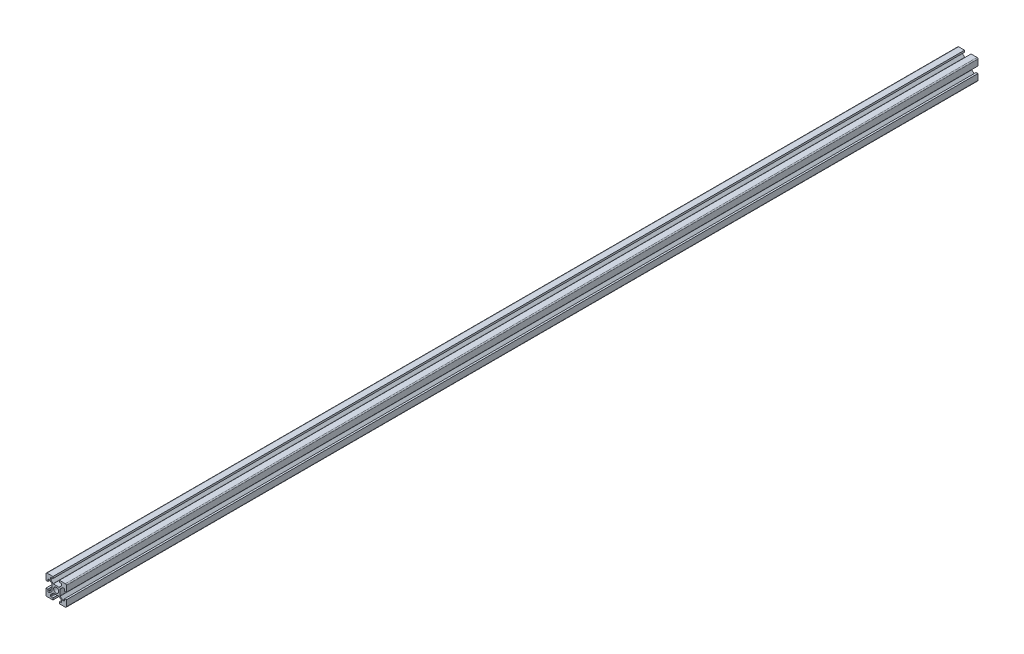
SolidWorks part; units mm, degrees
material "1060 Alloy"
ref_plane "Front Plane" through (0, 0, 0) normal (0, 0, 1) x (1, 0, 0)
ref_plane "Top Plane" through (0, 0, 0) normal (0, 1, 0) x (1, 0, 0)
ref_plane "Right Plane" through (0, 0, 0) normal (1, 0, 0) x (0, 0, -1)
sketch "Sketch1" plane through (0, 0, 0) normal (0, 0, 1) x (1, 0, 0)
  line L0 (20, 0) -> (-8.059, 28.059) construction
  line L1 (0, 0) -> (6.8, 0)
  line L2 (0, 0) -> (0, 6.8)
  line L3 (0, 20) -> (6.8, 20)
  line L4 (20, 0) -> (20, 6.8)
  line L5 (6.8, 20) -> (6.8, 18.2)
  line L6 (20, 20) -> (8.2322, 8.2322) construction
  line L7 (12.95, 6.1) -> (7.05, 6.1)
  line L8 (13.9, 7.05) -> (13.9, 12.95)
  line L9 (12.95, 13.9) -> (7.05, 13.9)
  line L10 (6.1, 7.05) -> (6.1, 12.95)
  line L11 (13.9, 6.1) -> (6.1, 13.9) construction
  line L12 (13.9, 13.9) -> (6.1, 6.1) construction
  line L13 (4.55, 16.4) -> (7.05, 13.9)
  line L14 (13.2, 18.2) -> (13.2, 20)
  line L15 (1.8, 6.8) -> (0, 6.8)
  line L16 (0, 13.2) -> (0, 20)
  line L17 (0, 13.2) -> (1.8, 13.2)
  line L18 (10, 10) -> (10, 13.9) construction
  line L19 (16.4, 4.55) -> (13.9, 7.05)
  line L20 (4.55, 16.4) -> (4.55, 18.2)
  line L21 (4.55, 18.2) -> (6.8, 18.2)
  line L22 (13.2, 18.2) -> (15.45, 18.2)
  line L23 (15.45, 18.2) -> (15.45, 16.4)
  line L24 (15.45, 16.4) -> (12.95, 13.9)
  line L25 (16.4, 4.55) -> (18.2, 4.55)
  line L26 (18.2, 4.55) -> (18.2, 6.8)
  line L27 (20, 6.8) -> (18.2, 6.8)
  line L28 (18.2, 13.2) -> (20, 13.2)
  line L29 (18.2, 13.2) -> (18.2, 15.45)
  line L30 (18.2, 15.45) -> (16.4, 15.45)
  line L31 (16.4, 15.45) -> (13.9, 12.95)
  line L32 (1.8, 4.55) -> (3.6, 4.55)
  line L33 (3.6, 15.45) -> (6.1, 12.95)
  line L34 (3.6, 15.45) -> (1.8, 15.45)
  line L35 (1.8, 15.45) -> (1.8, 13.2)
  line L36 (0, 13.2) -> (1.8, 13.2)
  line L37 (1.8, 6.8) -> (0, 6.8)
  line L38 (3.6, 4.55) -> (6.1, 7.05)
  line L39 (1.8, 6.8) -> (1.8, 4.55)
  line L40 (15.45, 3.6) -> (12.95, 6.1)
  line L41 (4.55, 3.6) -> (7.05, 6.1)
  line L42 (4.55, 1.8) -> (4.55, 3.6)
  line L43 (6.8, 1.8) -> (4.55, 1.8)
  line L44 (6.8, 1.8) -> (6.8, 0)
  line L45 (15.45, 3.6) -> (15.45, 1.8)
  line L46 (15.45, 1.8) -> (13.2, 1.8)
  line L47 (13.2, 0) -> (13.2, 1.8)
  line L48 (13.2, 20) -> (20, 20)
  line L49 (20, 13.2) -> (20, 20)
  line L50 (13.2, 0) -> (20, 0)
  line L51 (6.1, 6.1) -> (-5.5045, -5.5045) construction
  circle A0 centre (10, 10) radius 2.5
  point P25 (10, 16.4)
  point P39 (13.2, 19.1)
  point P46 (0.9, 6.8)
  dimension "D3" = 5
  dimension "D2" = 20
  dimension "D4" = 7.8
  dimension "D5" = 7.8
  dimension "D6" = 6.8
  dimension "D7" = 6.8
  dimension "D8" = 1.8
  dimension "D9" = 10.9
  dimension "D10" = 1.8
  dimension "D11" = 10.9
  dimension "D12" = 20
extrude "Boss-Extrude1" add sketch "Sketch1" along normal blind 894.4 contours L47 L50 L4 L27 L26 L25 L19 L8 L31 L30 L29 L28 L49 L48 L14 L22 L23 L24 L9 L13 L20 L21 L5 L3 L16 L17 L35 L34 L33 L10 L38 L32 L39 L15 L2 L1 L44 L43 L42 L41 L7 L40 L45 L46 A0
fillet "Fillet1" radius 1 4 edges at (20, 20, 447.2) (20, 0, 447.2) (0, 0, 447.2) (0, 20, 447.2)
fillet "Fillet2" radius 0.5 6 edges at (4.55, 18.2, 447.2) (4.55, 16.4, 447.2) (7.05, 13.9, 447.2) (15.45, 18.2, 447.2) (15.45, 16.4, 447.2) (12.95, 13.9, 447.2)
fillet "Fillet3" radius 0.5 6 edges at (18.2, 15.45, 447.2) (16.4, 15.45, 447.2) (13.9, 12.95, 447.2) (18.2, 4.55, 447.2) (13.9, 7.05, 447.2) (16.4, 4.55, 447.2)
fillet "Fillet4" radius 0.5 6 edges at (1.8, 15.45, 447.2) (3.6, 15.45, 447.2) (6.1, 12.95, 447.2) (3.6, 4.55, 447.2) (1.8, 4.55, 447.2) (6.1, 7.05, 447.2)
fillet "Fillet5" radius 0.5 6 edges at (7.05, 6.1, 447.2) (4.55, 3.6, 447.2) (4.55, 1.8, 447.2) (15.45, 1.8, 447.2) (15.45, 3.6, 447.2) (12.95, 6.1, 447.2)
